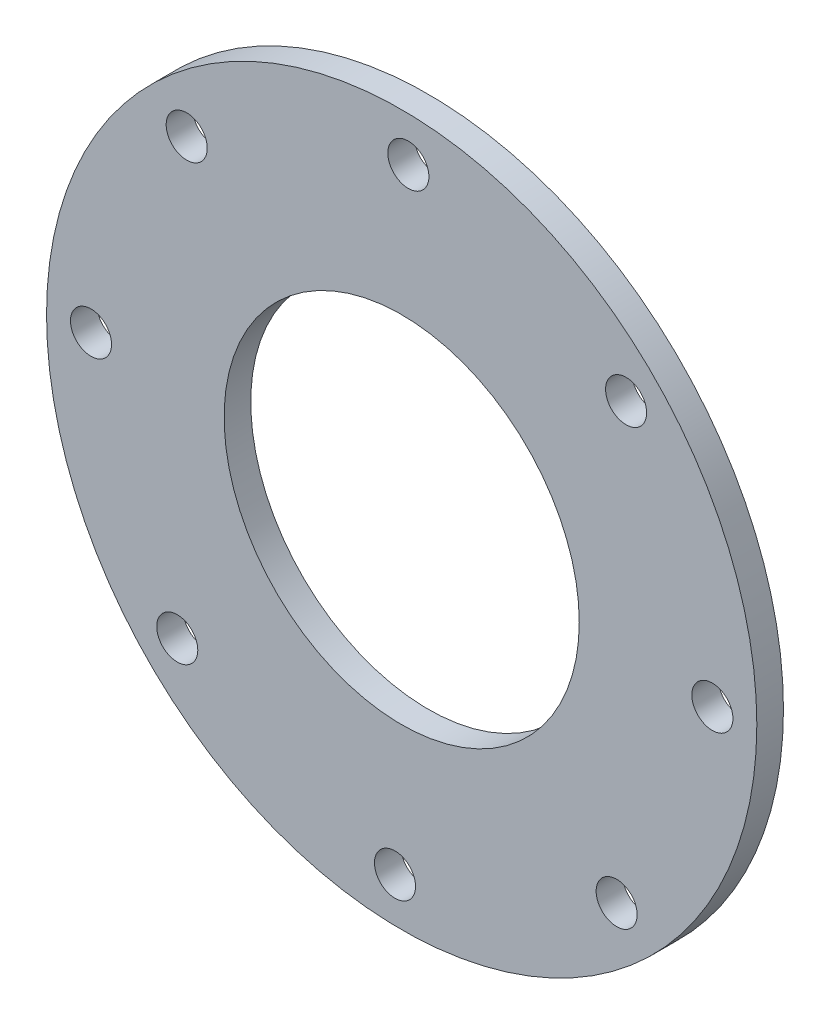
SolidWorks part; units mm, degrees
ref_plane "Front Plane" through (0, 0, 0) normal (0, 0, 1) x (1, 0, 0)
ref_plane "Top Plane" through (0, 0, 0) normal (0, 1, 0) x (1, 0, 0)
ref_plane "Right Plane" through (0, 0, 0) normal (1, 0, 0) x (0, 0, -1)
sketch "Sketch1" plane through (0, 0, 0) normal (0, 0, 1) x (1, 0, 0)
  circle A0 centre (0, 0) radius 140 construction
  circle A1 centre (0, 0) radius 160
  circle A2 centre (0, 0) radius 80
  circle A3 centre (-96.8441, 101.1001) radius 9.25
  circle A4 centre (3.0094, 139.9677) radius 9.25
  circle A5 centre (101.1001, 96.8441) radius 9.25
  circle A6 centre (139.9677, -3.0094) radius 9.25
  circle A7 centre (96.8441, -101.1001) radius 9.25
  circle A8 centre (-3.0094, -139.9677) radius 9.25
  circle A9 centre (-101.1001, -96.8441) radius 9.25
  circle A10 centre (-139.9677, 3.0094) radius 9.25
  point P23 (0, 0)
  dimension "D1" = 320
  dimension "D2" = 160
  dimension "D3" = 280
  dimension "D4" = 18.5
  dimension "D5" = 8
extrude "Boss-Extrude1" add sketch "Sketch1" along normal mid plane 12
